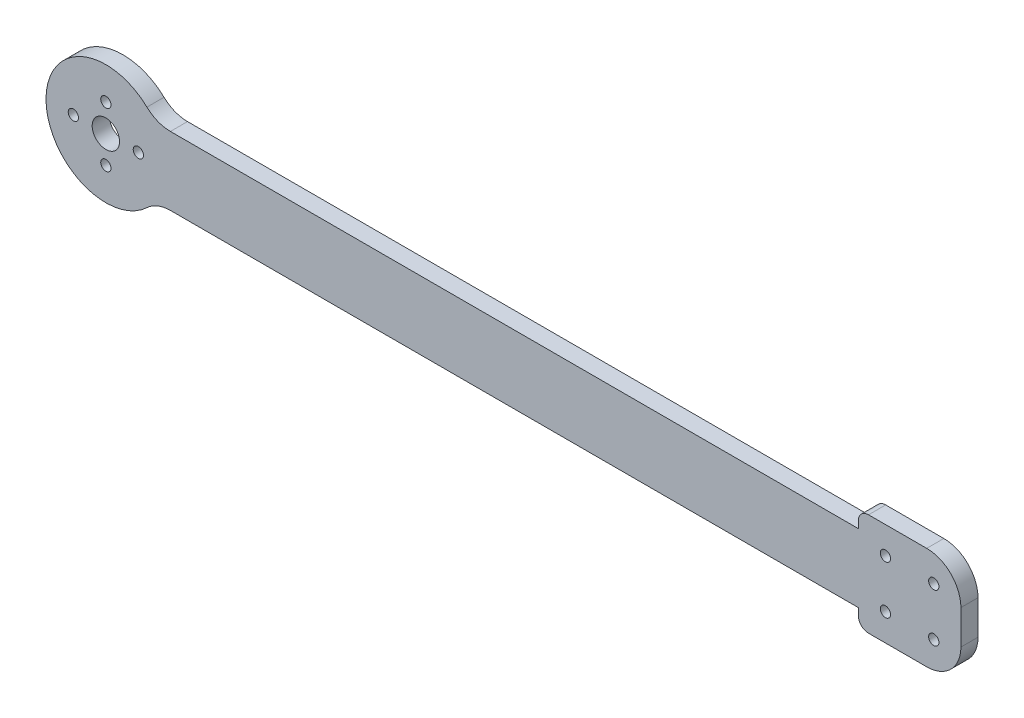
SolidWorks part; units mm, degrees
ref_plane "Front Plane" through (0, 0, 0) normal (0, 0, 1) x (1, 0, 0)
ref_plane "Top Plane" through (0, 0, 0) normal (0, 1, 0) x (1, 0, 0)
ref_plane "Right Plane" through (0, 0, 0) normal (1, 0, 0) x (0, 0, -1)
sketch "Sketch1" plane through (0, 0, 0) normal (0, 0, 1) x (1, 0, 0)
  line L0 (-27.0033, 0) -> (25.1562, 0) construction
  line L1 (0, 12.5437) -> (0, -12.9283) construction
  line L2 (220, -10) -> (220, -12)
  line L3 (18.8746, -10) -> (220, -10)
  line L4 (18.8746, 10) -> (220, 10)
  line L5 (220, 15) -> (250, -15) construction
  line L6 (250, -5) -> (250, 5)
  line L7 (240, 15) -> (223, 15)
  line L8 (240, -15) -> (223, -15)
  line L9 (220, 12) -> (220, 10)
  line L10 (250, 15) -> (220, -15) construction
  circle A1 centre (0, 0) radius 4
  circle A3 centre (9.5, 0) radius 1.5
  circle A5 centre (-9.5, 0) radius 1.5
  circle A7 centre (0, 8) radius 1.5
  circle A8 centre (0, -8) radius 1.5
  arc A9 (12.0111, 12.7273) -> (12.0111, -12.7273) centre (0, 0) ccw
  circle A10 centre (235, 0) radius 10 construction
  circle A11 centre (227.9289, 7.0711) radius 1.5
  circle A12 centre (242.0711, -7.0711) radius 1.5
  circle A13 centre (242.0711, 7.0711) radius 1.5
  circle A14 centre (227.9289, -7.0711) radius 1.5
  arc A15 (240, 15) -> (250, 5) centre (240, 5) cw
  arc A16 (250, -5) -> (240, -15) centre (240, -5) cw
  arc A17 (12.0111, -12.7273) -> (18.8746, -10) centre (18.8746, -20) cw
  arc A18 (18.8746, 10) -> (12.0111, 12.7273) centre (18.8746, 20) cw
  arc A19 (223, -15) -> (220, -12) centre (223, -12) cw
  arc A20 (220, 12) -> (223, 15) centre (223, 12) cw
  point P14 (0, 0)
  dimension "D1" = 35
  dimension "D2" = 3
  dimension "D5" = 8
  dimension "D6" = 10
  dimension "D7" = 3
  dimension "D3" = 19
  dimension "D4" = 16
  dimension "D9" = 30
extrude "Boss-Extrude2" add sketch "Sketch1" along normal blind 5
